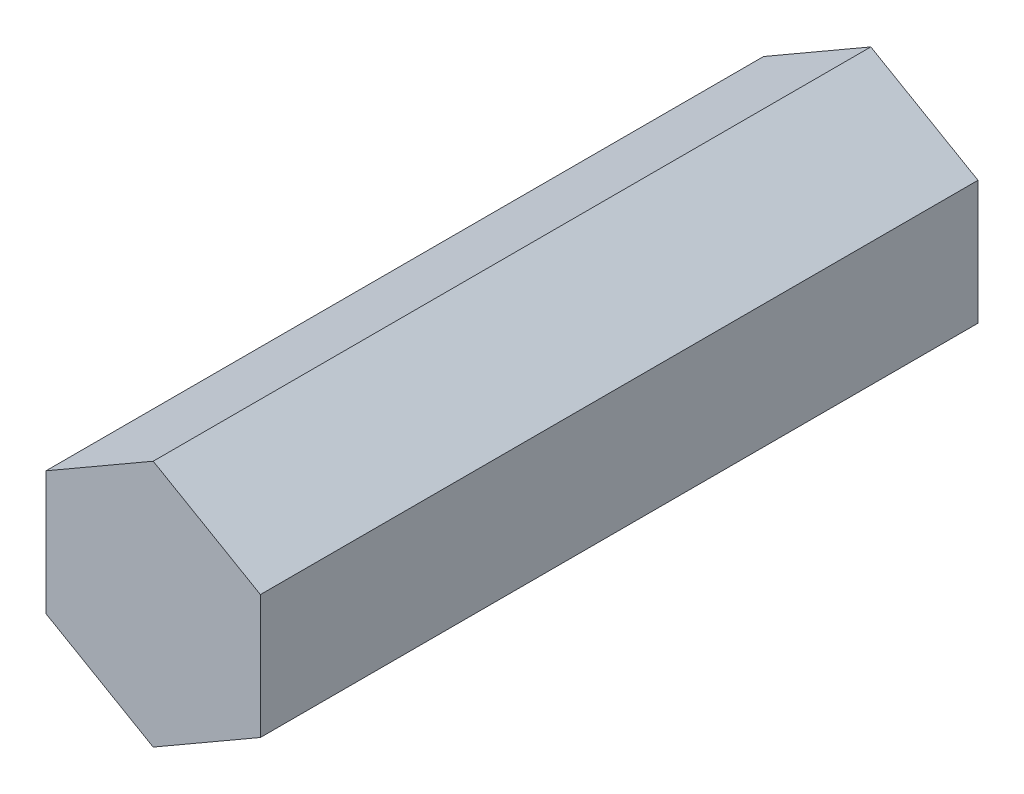
SolidWorks part; units mm, degrees
ref_plane "Front Plane" through (0, 0, 0) normal (0, 0, 1) x (1, 0, 0)
ref_plane "Top Plane" through (0, 0, 0) normal (0, 1, 0) x (1, 0, 0)
ref_plane "Right Plane" through (0, 0, 0) normal (1, 0, 0) x (0, 0, -1)
sketch "Sketch1" plane through (0, 0, 0) normal (0, 0, 1) x (1, 0, 0)
  line L1 (0, 6.9) -> (-5.9756, 3.45)
  line L2 (-5.9756, 3.45) -> (-5.9756, -3.45)
  line L3 (-5.9756, -3.45) -> (0, -6.9)
  line L4 (0, -6.9) -> (5.9756, -3.45)
  line L5 (5.9756, -3.45) -> (5.9756, 3.45)
  line L6 (5.9756, 3.45) -> (0, 6.9)
  circle A0 centre (0, 0) radius 5.9756 construction
  dimension "D1" = 6.9
extrude "Boss-Extrude1" add sketch "Sketch1" along normal blind 40
